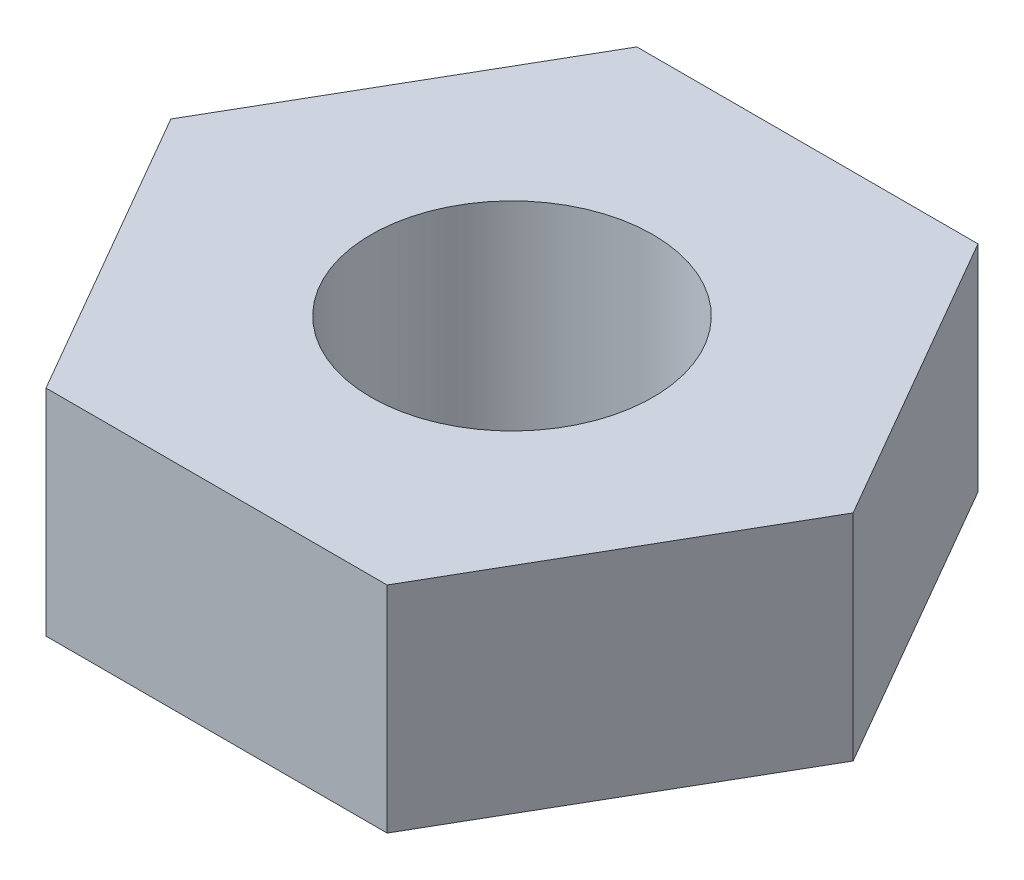
SolidWorks part; units mm, degrees
material "Acier allié"
ref_plane "Face" through (0, 0, 0) normal (0, 0, 1) x (1, 0, 0)
ref_plane "Dessus" through (0, 0, 0) normal (0, 1, 0) x (1, 0, 0)
ref_plane "Droite" through (0, 0, 0) normal (1, 0, 0) x (0, 0, -1)
sketch "Esquisse1" plane through (0, 0, 0) normal (0, 1, 0) x (1, 0, 0)
  line L1 (2.5205, 4.3656) -> (-2.5205, 4.3656)
  line L2 (-2.5205, 4.3656) -> (-5.041, 0)
  line L3 (-5.041, 0) -> (-2.5205, -4.3656)
  line L4 (-2.5205, -4.3656) -> (2.5205, -4.3656)
  line L5 (2.5205, -4.3656) -> (5.041, 0)
  line L6 (5.041, 0) -> (2.5205, 4.3656)
  circle A0 centre (0, 0) radius 4.3656 construction
  dimension "D1" = 8.7312
extrude "Boss.-Extru.1" add sketch "Esquisse1" along normal blind 3.175
sketch "Esquisse2" plane through (0, 3.175, 0) normal (0, 1, 0) x (1, 0, 0)
  circle A0 centre (0, 0) radius 2.0828
  dimension "D1" = 4.1656
extrude "Enlèv. mat.-Extru.1" cut sketch "Esquisse2" against normal through all
cosmetic thread "Représentation de filetage1" parameters "D2"=4.191
equation "\"W\"=11/32"
equation "\"D1@Esquisse1\"=\"W\""
equation "\"H\"=1/8"
equation "\"D1@Boss.-Extru.1\"=\"H\""
equation "\"D\"=0.164"
equation "\"D1@Esquisse2\"=\"D\""
equation "\"D2@Représentation de filetage1\"=\"D\"+0.001"
